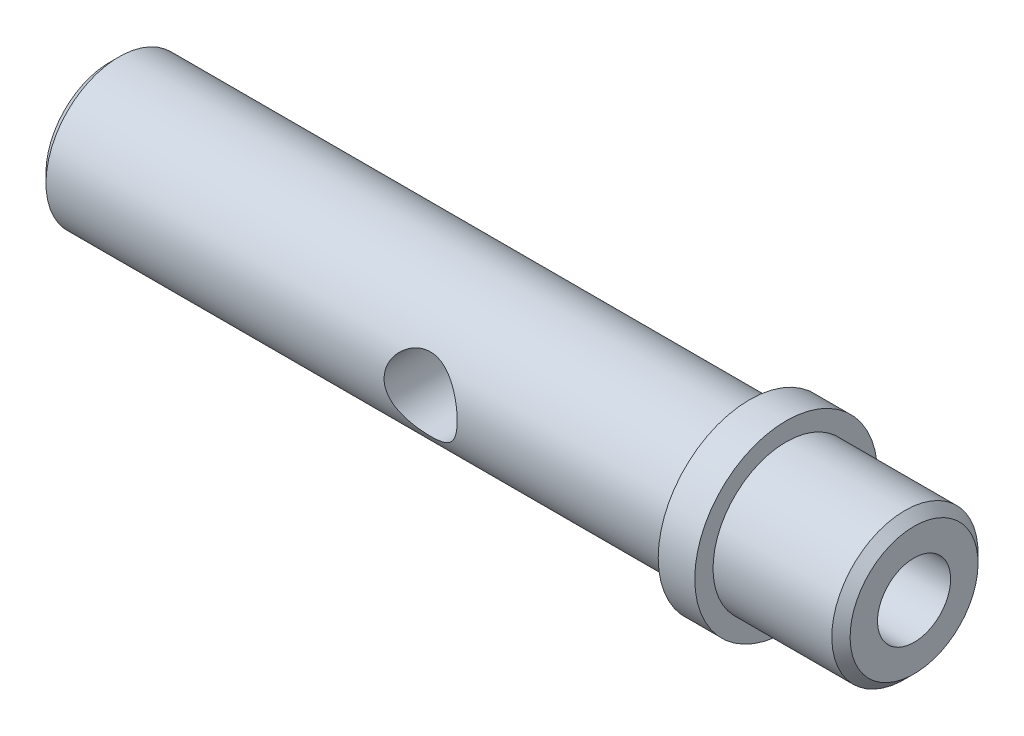
SolidWorks part; units mm, degrees
ref_plane "前视基准面" through (0, 0, 0) normal (0, 0, 1) x (1, 0, 0)
ref_plane "上视基准面" through (0, 0, 0) normal (0, 1, 0) x (1, 0, 0)
ref_plane "右视基准面" through (0, 0, 0) normal (1, 0, 0) x (0, 0, -1)
sketch "草图1" plane through (0, 0, 0) normal (0, 0, 1) x (1, 0, 0)
  line L0 (-16.7018, 0) -> (17, 0)
  line L1 (0, 0) -> (0, 2)
  line L2 (0, 2) -> (4, 2)
  line L3 (4, 2) -> (4, 4)
  line L4 (4, 4) -> (17, 4)
  line L5 (17, 4) -> (17, 2)
  line L6 (17, 2) -> (21, 2)
  line L7 (21, 2) -> (21, 0)
  line L8 (21, 0) -> (17, 0)
  dimension "D1" = 2
  dimension "D2" = 2
  dimension "D3" = 4
  dimension "D4" = 13
  dimension "D5" = 4
  dimension "D6" = 4
revolve "旋转2" add sketch "草图1" angle 360 about L0
sketch "草图2" plane through (0, 0, 0) normal (0, 0, 1) x (1, 0, 0)
  line L0 (17, 4) -> (4, 4)
  line L1 (12.5, -5.8272) -> (8.5, -5.8272)
  line L2 (12.5, -5.8272) -> (12.5, 5.8272)
  line L3 (12.5, 5.8272) -> (8.5, 5.8272)
  line L4 (8.5, -5.8272) -> (8.5, 5.8272)
  line L6 (12.5, 5.8272) -> (11.8729, 4) construction
  line L7 (17, 4) -> (4, 4) construction
  line L8 (10.5, 4) -> (10.5, 4.8104)
  line L9 (9.1271, 4) -> (8.5, 5.8272) construction
  dimension "D2" = 4
  dimension "D3" = 2
extrude "切除-拉伸1" cut sketch "草图2" against normal blind 10 from offset 3.5 contours L4 L1 L2 L0 offset against normal yes
sketch "草图3" plane through (0, 0, 0) normal (0, 1, 0) x (1, 0, 0)
  line L0 (8.5, 3.5) -> (12.5, 3.5) construction
  line L1 (12.5, 13.3353) -> (8.5, 13.3353)
  line L2 (12.5, 13.3353) -> (12.5, -6.3353)
  line L3 (12.5, -6.3353) -> (8.5, -6.3353)
  line L4 (8.5, 13.3353) -> (8.5, -6.3353)
  line L5 (12.5, 13.3353) -> (8.5, -6.3353) construction
  line L6 (12.5, -6.3353) -> (8.5, 13.3353) construction
  point P0 (10.5, 3.5)
  dimension "D1" = 4
extrude "切除-拉伸2" cut sketch "草图3" against normal blind 10 from offset 3.5 offset against normal yes
sketch "草图4" plane through (21, 0, 0) normal (1, 0, 0) x (0, 0, -1)
  circle A1 centre (0, 0) radius 2
  circle A2 centre (0, 0) radius 2
  circle A3 centre (0, 0) radius 4
  circle A4 centre (0, 0) radius 4
  dimension "D1" = 0
  dimension "D2" = 0
extrude "切除-拉伸3" cut sketch "草图4" against normal blind 29
sketch "草图5" plane through (0, 0, 0) normal (0, 0, 1) x (1, 0, 0)
  circle A0 centre (10.5, 0) radius 1
  dimension "D1" = 2
extrude "切除-拉伸4" cut sketch "草图5" against normal mid plane 10
sketch "草图6" plane through (21, 0, 0) normal (1, 0, 0) x (0, 0, -1)
  circle A1 centre (0, 0) radius 2
  circle A2 centre (0, 0) radius 2
  dimension "D1" = 0
extrude "凸台-拉伸1" add sketch "草图6" along normal blind 1
sketch "草图7" plane through (22, 0, 0) normal (1, 0, 0) x (0, 0, -1)
  circle A0 centre (0, 0) radius 2.5
  circle A1 centre (0, 0) radius 2
  circle A2 centre (0, 0) radius 2
  dimension "D1" = 0
  dimension "D2" = 0.5
extrude "凸台-拉伸2" add sketch "草图7" against normal blind 1 from offset 3.5 offset against normal yes
sketch "草图8" plane through (22, 0, 0) normal (1, 0, 0) x (0, 0, -1)
  circle A0 centre (0, 0) radius 1
  dimension "D1" = 2
extrude "切除-拉伸5" cut sketch "草图8" against normal blind 5
chamfer "倒角1" distance 0.25 1 edges at (22, 2, 0)
chamfer "倒角2" distance 0.25 1 edges at (0, -2, 0)
